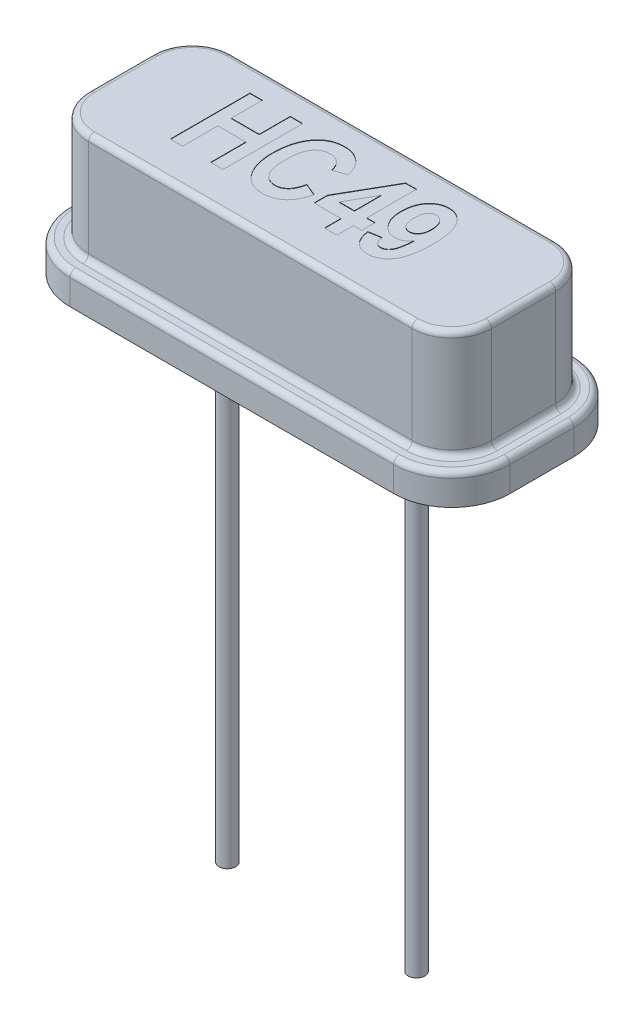
SolidWorks part; units mm, degrees
ref_plane "Front Plane" through (0, 0, 0) normal (0, 0, 1) x (1, 0, 0)
ref_plane "Top Plane" through (0, 0, 0) normal (0, 1, 0) x (1, 0, 0)
ref_plane "Right Plane" through (0, 0, 0) normal (1, 0, 0) x (0, 0, -1)
sketch "Sketch1" plane through (0, 0, 0) normal (0, 1, 0) x (1, 0, 0)
  line L0 (5.675, -0.825) -> (5.675, 0.825)
  line L1 (0, 0) -> (-5.675, 0) construction
  line L2 (0, 0) -> (0, 2.325) construction
  line L3 (4.175, 2.325) -> (-4.175, 2.325)
  line L4 (-5.675, -0.825) -> (-5.675, 0.825)
  line L5 (4.175, -2.325) -> (-4.175, -2.325)
  arc A0 (4.175, -2.325) -> (5.675, -0.825) centre (4.175, -0.825) ccw
  arc A1 (5.675, 0.825) -> (4.175, 2.325) centre (4.175, 0.825) ccw
  arc A2 (-4.175, -2.325) -> (-5.675, -0.825) centre (-4.175, -0.825) cw
  arc A3 (-4.175, 2.325) -> (-5.675, 0.825) centre (-4.175, 0.825) ccw
  point P8 (5.675, 0)
  point P11 (5.675, -2.325)
  point P14 (5.675, 2.325)
  point P17 (-5.675, -2.325)
  point P20 (-5.675, 2.325)
  dimension "D3" = 1.5
  dimension "D1" = 5.675
  dimension "D2" = 2.325
extrude "Boss-Extrude1" add sketch "Sketch1" along normal blind 0.8
sketch "Sketch2" plane through (0, 0.8, 0) normal (0, 1, 0) x (1, 0, 0)
  line L20 (-5.2, 0.825) -> (-5.2, -0.825)
  line L21 (-4.175, -1.85) -> (4.175, -1.85)
  line L22 (5.2, -0.825) -> (5.2, 0.825)
  line L23 (4.175, 1.85) -> (-4.175, 1.85)
  line L24 (-5.2, 0.825) -> (-5.2, -0.825)
  line L25 (-4.175, -1.85) -> (4.175, -1.85)
  line L26 (5.2, -0.825) -> (5.2, 0.825)
  line L27 (4.175, 1.85) -> (-4.175, 1.85)
  arc A24 (-5.2, -0.825) -> (-4.175, -1.85) centre (-4.175, -0.825) ccw
  arc A25 (4.175, -1.85) -> (5.2, -0.825) centre (4.175, -0.825) ccw
  arc A26 (5.2, 0.825) -> (4.175, 1.85) centre (4.175, 0.825) ccw
  arc A27 (-4.175, 1.85) -> (-5.2, 0.825) centre (-4.175, 0.825) ccw
  arc A28 (-5.2, -0.825) -> (-4.175, -1.85) centre (-4.175, -0.825) ccw
  arc A29 (4.175, -1.85) -> (5.2, -0.825) centre (4.175, -0.825) ccw
  arc A30 (5.2, 0.825) -> (4.175, 1.85) centre (4.175, 0.825) ccw
  arc A31 (-4.175, 1.85) -> (-5.2, 0.825) centre (-4.175, 0.825) ccw
  dimension "D1" = 0.475
extrude "Boss-Extrude2" add sketch "Sketch2" along normal blind 2.8
fillet "Fillet1" radius 0.15 24 edges at (-4.8998, 0.8, -1.5498) (0, 0.8, -1.85) (4.8998, 0.8, -1.5498) (5.2, 0.8, 0) (4.8998, 0.8, 1.5498) (0, 0.8, 1.85) (-4.8998, 0.8, 1.5498) (-5.2357, 0.8, -1.8857) (0, 0.8, -2.325) (5.2357, 0.8, -1.8857) (5.675, 0.8, 0) (5.2357, 0.8, 1.8857) (0, 0.8, 2.325) (-5.2357, 0.8, 1.8857) (-4.8998, 3.6, 1.5498) (-5.2, 3.6, 0) (-4.8998, 3.6, -1.5498) (0, 3.6, -1.85) (4.8998, 3.6, -1.5498) (5.2, 3.6, 0) (4.8998, 3.6, 1.5498) (-5.2, 0.8, 0) (-5.675, 0.8, 0) (0, 3.6, 1.85)
sketch "Sketch3" plane through (0, 0, 0) normal (0, -1, 0) x (1, 0, 0)
  line L0 (0, 0) -> (0, 3.9327) construction
  line L1 (0, 0) -> (6.9613, 0) construction
  line L2 (2.44, 0) -> (2.44, 3.9327) construction
  line L3 (-2.44, 0) -> (-2.44, 3.9327) construction
  circle A0 centre (-2.44, 0) radius 0.215
  circle A1 centre (2.44, 0) radius 0.215
  dimension "D3" = 0.43
  dimension "D1" = 2.44
  dimension "D2" = 2.44
extrude "Boss-Extrude3" add sketch "Sketch3" along normal blind 12.7
sketch "Sketch4" plane through (0, 3.6, 0) normal (0, 1, 0) x (1, 0, 0)
  text T0 "<b>HC49</b>" font "Arial Narrow" height in points 8
extrude "Cut-Extrude1" cut sketch "Sketch4" against normal blind 0.01
sketch "Sketch5" plane through (0, 0, 0) normal (0, -1, 0) x (1, 0, 0)
  circle A31 centre (-2.44, 0) radius 0.415
  circle A32 centre (-2.44, 0) radius 0.415
  circle A33 centre (-2.44, 0) radius 0.215 construction
  circle A34 centre (2.44, 0) radius 0.415
  circle A35 centre (2.44, 0) radius 0.415
  circle A36 centre (2.44, 0) radius 0.215 construction
  circle A37 centre (-2.44, 0) radius 0.215
  circle A38 centre (2.44, 0) radius 0.215
  dimension "D1" = 0.2
  dimension "D2" = 0.2
extrude "Cut-Extrude3" cut sketch "Sketch5" against normal blind 0.02
